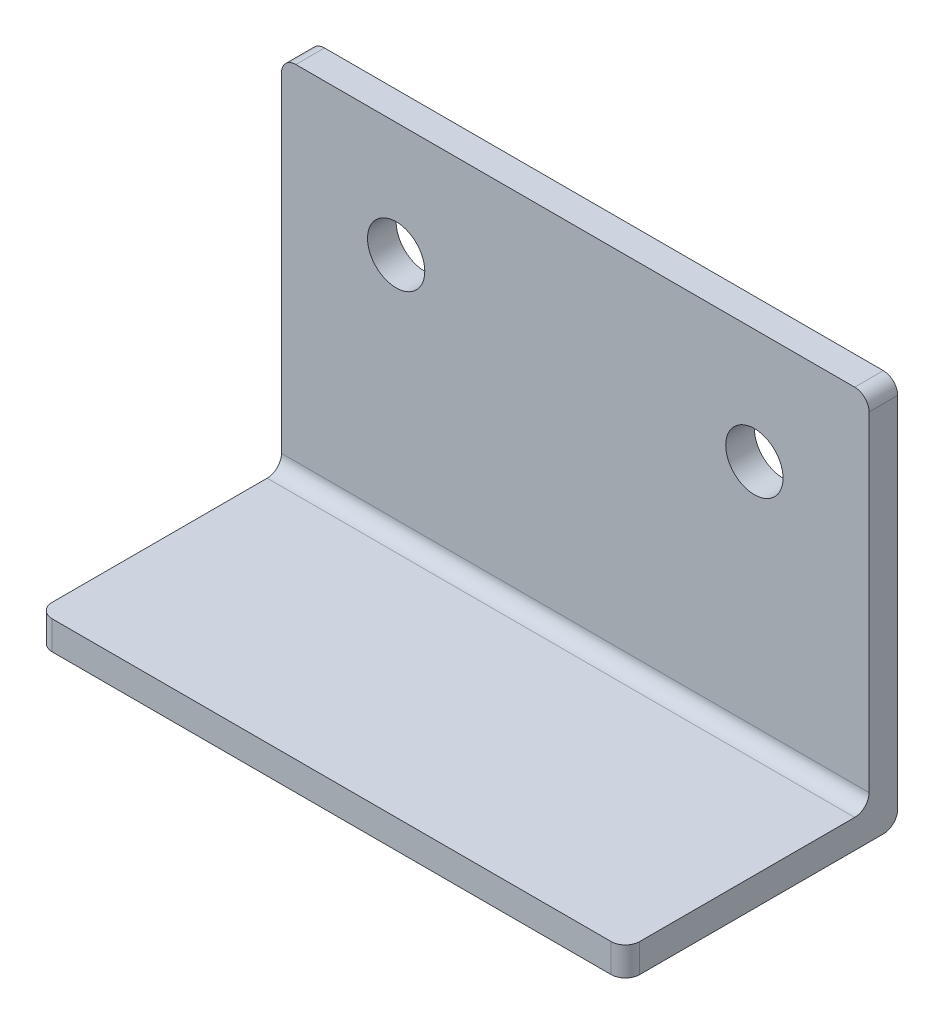
SolidWorks part; units mm, degrees
ref_plane "前视基准面" through (0, 0, 0) normal (0, 0, 1) x (1, 0, 0)
ref_plane "上视基准面" through (0, 0, 0) normal (0, 1, 0) x (1, 0, 0)
ref_plane "右视基准面" through (0, 0, 0) normal (1, 0, 0) x (0, 0, -1)
sketch "草图1" plane through (0, 0, 0) normal (0, 1, 0) x (1, 0, 0)
  line L1 (-20.5, 9.5) -> (20.5, 9.5)
  line L2 (-20.5, 9.5) -> (-20.5, -9.5)
  line L3 (-20.5, -9.5) -> (20.5, -9.5)
  line L4 (20.5, 9.5) -> (20.5, -9.5)
  line L5 (-20.5, 9.5) -> (20.5, -9.5) construction
  line L6 (-20.5, -9.5) -> (20.5, 9.5) construction
  point P0 (0, 0)
  dimension "D1" = 19
  dimension "D2" = 41
extrude "凸台-拉伸2" add sketch "草图1" along normal blind 2
sketch "草图2" plane through (0, 2, 0) normal (0, 1, 0) x (1, 0, 0)
  line L0 (20.5, -9.5) -> (20.5, 9.5) construction
  line L1 (-20.5, 9.5) -> (20.5, 9.5)
  line L2 (-20.5, 9.5) -> (-20.5, 7.5)
  line L3 (-20.5, 7.5) -> (20.5, 7.5)
  line L4 (20.5, 9.5) -> (20.5, 7.5)
  dimension "D1" = 2
extrude "凸台-拉伸3" add sketch "草图2" along normal blind 25
sketch "草图3" plane through (0, 0, -7.5) normal (0, 0, 1) x (1, 0, 0)
  line L0 (-20.5, 14.5) -> (20.5, 14.5) construction
  line L1 (-20.5, 27) -> (-20.5, 2) construction
  line L2 (20.5, 27) -> (20.5, 2) construction
  line L3 (0, 27) -> (0, 2) construction
  line L4 (-20.5, 27) -> (20.5, 27) construction
  line L5 (-20.5, 2) -> (20.5, 2) construction
  circle A0 centre (-12.5, 19) radius 2
  circle A1 centre (12.5, 19) radius 2
  dimension "D1" = 12.5
  dimension "D2" = 8
extrude "切除-拉伸1" cut sketch "草图3" against normal blind 25
fillet "圆角1" radius 1 1 edges at (0, 2, -7.5)
fillet "圆角2" radius 1 1 edges at (0, 0, -9.5)
fillet "圆角3" radius 1 1 edges at (-20.5, 1, 9.5)
fillet "圆角4" radius 1 1 edges at (20.5, 1, 9.5)
fillet "圆角5" radius 1 1 edges at (-20.5, 27, -8.5)
fillet "圆角6" radius 1 1 edges at (20.5, 27, -8.5)
